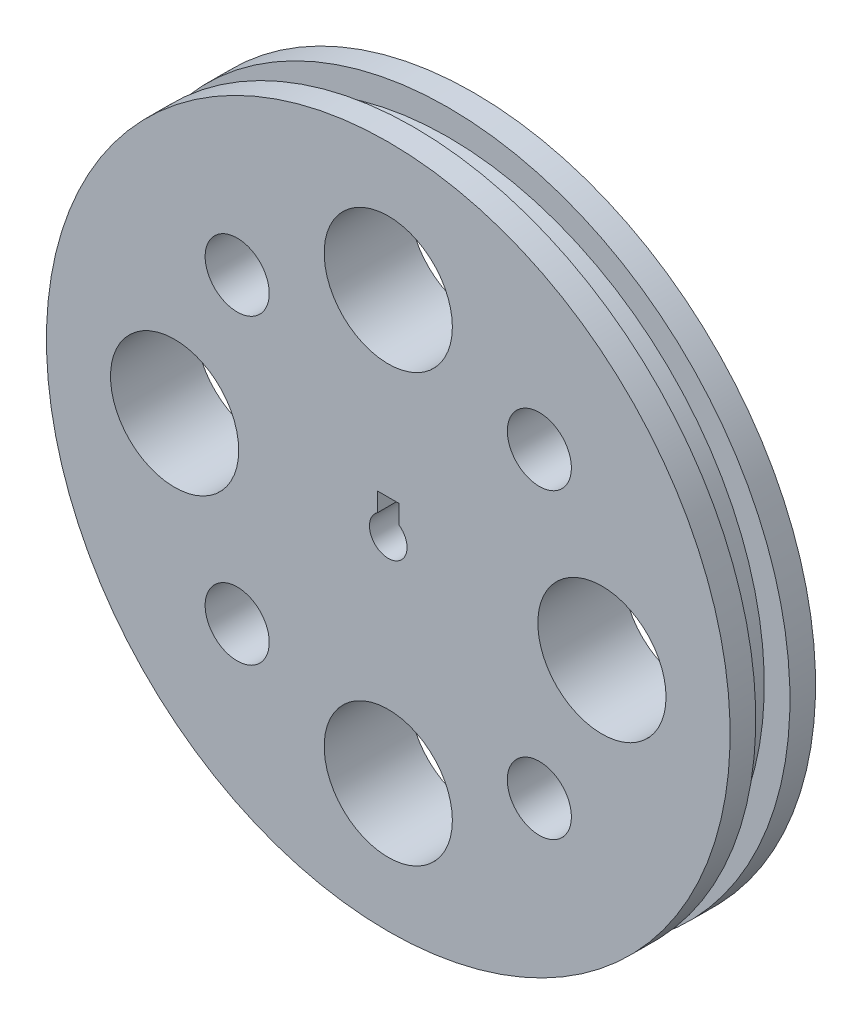
SolidWorks part; units mm, degrees
ref_plane "Front Plane" through (0, 0, 0) normal (0, 0, 1) x (1, 0, 0)
ref_plane "Top Plane" through (0, 0, 0) normal (0, 1, 0) x (1, 0, 0)
ref_plane "Right Plane" through (0, 0, 0) normal (1, 0, 0) x (0, 0, -1)
sketch "Sketch1" plane through (0, 0, 0) normal (1, 0, 0) x (0, 0, -1)
  line L0 (0, 0) -> (-12.7, 0)
  line L1 (-12.7, 0) -> (-12.7, 101.6)
  line L2 (-12.7, 101.6) -> (-5.08, 101.6)
  line L3 (-5.08, 101.6) -> (-5.08, 93.98)
  line L4 (-5.08, 93.98) -> (5.08, 93.98)
  line L5 (5.08, 93.98) -> (5.08, 101.6)
  line L6 (5.08, 101.6) -> (12.7, 101.6)
  line L7 (12.7, 101.6) -> (12.7, 0)
  line L8 (12.7, 0) -> (0, 0)
  dimension "D1" = 101.6
  dimension "D2" = 7.62
  dimension "D3" = 7.62
  dimension "D4" = 10.16
  dimension "D5" = 12.7
  dimension "D6" = 93.98
revolve "Revolve2" add sketch "Sketch1" angle 360 about L0
sketch "Sketch5" plane through (0, 0, 0) normal (0, 0, 1) x (1, 0, 0)
  line L0 (-101.6, 0) -> (101.6, 0) construction
  line L1 (0, 101.6) -> (0, -101.6) construction
  line L2 (0, 0) -> (71.842, -71.842) construction
  circle A0 centre (0, 0) radius 101.6 construction
  circle A1 centre (0, 0) radius 63.5 construction
  circle A2 centre (0, -63.5) radius 19.05
  circle A3 centre (44.9013, -44.9013) radius 9.525
  circle A4 centre (-63.5, 0) radius 19.05
  circle A5 centre (-44.9013, -44.9013) radius 9.525
  circle A6 centre (0, 63.5) radius 19.05
  circle A7 centre (-44.9013, 44.9013) radius 9.525
  circle A8 centre (63.5, 0) radius 19.05
  circle A9 centre (44.9013, 44.9013) radius 9.525
  dimension "D1" = 127
  dimension "D3" = 38.1
  dimension "D4" = 19.05
  dimension "D2" = 45
  dimension "D5" = 4
extrude "Cut-Extrude1" cut sketch "Sketch5" against normal through all both and the other way through all
sketch "Sketch6" plane through (0, 0, 0) normal (0, 0, 1) x (1, 0, 0)
  circle A0 centre (0, 0) radius 5.588
  point P7 (0, 0)
  point P8 (0, 0)
  dimension "D1" = 11.176
extrude "Cut-Extrude5" cut sketch "Sketch6" against normal through all both and the other way through all
sketch "Sketch8" plane through (0, 0, 0) normal (0, 0, 1) x (1, 0, 0)
  line L0 (-3.175, 4.5984) -> (-3.175, 10.16)
  line L1 (-3.175, 10.16) -> (3.175, 10.16)
  line L2 (3.175, 10.16) -> (3.175, 4.5984)
  line L3 (3.175, 4.5984) -> (-3.175, 4.5984)
  circle A0 centre (0, 0) radius 5.588 construction
  point P5 (0, 0)
  point P7 (0, 0)
  dimension "D1" = 10.16
  dimension "D2" = 6.35
extrude "Cut-Extrude6" cut sketch "Sketch8" against normal through all both and the other way through all
